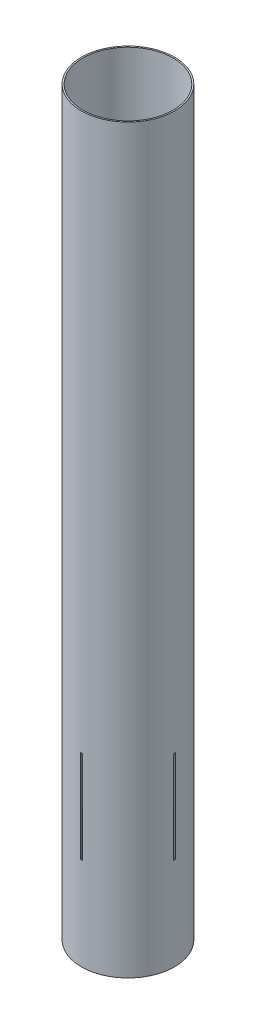
SolidWorks part; units mm, degrees
ref_plane "Front Plane" through (0, 0, 0) normal (0, 0, 1) x (1, 0, 0)
ref_plane "Top Plane" through (0, 0, 0) normal (0, 1, 0) x (1, 0, 0)
ref_plane "Right Plane" through (0, 0, 0) normal (1, 0, 0) x (0, 0, -1)
sketch "Sketch1" plane through (0, 0, 0) normal (0, 1, 0) x (1, 0, 0)
  circle A0 centre (0, 0) radius 51.1048
  circle A1 centre (0, 0) radius 49.53
  dimension "D1" = 99.06
  dimension "D2" = 102.2096
extrude "Boss-Extrude1" add sketch "Sketch1" along normal blind 812.8
ref_plane "Plane1" through (0, 101.6, 0) normal (0, -1, 0) x (-1, 0, 0)
sketch "Sketch2" plane through (0, 101.6, 0) normal (0, -1, 0) x (-1, 0, 0)
  line L0 (0, 51.1048) -> (0, -51.1048) construction
  line L1 (-1.1481, 51.7272) -> (-1.1481, 48.6338)
  line L2 (1.1481, 51.7272) -> (1.1481, 48.6338)
  line L3 (51.7272, 1.1481) -> (48.6338, 1.1481)
  line L4 (51.7272, -1.1481) -> (48.6338, -1.1481)
  line L5 (1.1481, -51.7272) -> (1.1481, -48.6338)
  line L6 (-1.1481, -51.7272) -> (-1.1481, -48.6338)
  line L7 (-51.7272, -1.1481) -> (-48.6338, -1.1481)
  line L8 (-51.7272, 1.1481) -> (-48.6338, 1.1481)
  circle A0 centre (0, 0) radius 51.1048 construction
  arc A1 (1.1481, 51.7272) -> (-1.1481, 51.7272) centre (0, 0) ccw
  arc A2 (1.1481, 48.6338) -> (-1.1481, 48.6338) centre (0, 0) ccw
  arc A3 (51.7272, -1.1481) -> (51.7272, 1.1481) centre (0, 0) ccw
  arc A4 (48.6338, -1.1481) -> (48.6338, 1.1481) centre (0, 0) ccw
  arc A5 (-1.1481, -51.7272) -> (1.1481, -51.7272) centre (0, 0) ccw
  arc A6 (-1.1481, -48.6338) -> (1.1481, -48.6338) centre (0, 0) ccw
  arc A7 (-51.7272, 1.1481) -> (-51.7272, -1.1481) centre (0, 0) ccw
  arc A8 (-48.6338, 1.1481) -> (-48.6338, -1.1481) centre (0, 0) ccw
  point P26 (0, 0)
  dimension "D1" = 1.1481
  dimension "D2" = 1.1481
  dimension "D3" = 4
extrude "Cut-Extrude1" cut sketch "Sketch2" against normal blind 101.6
